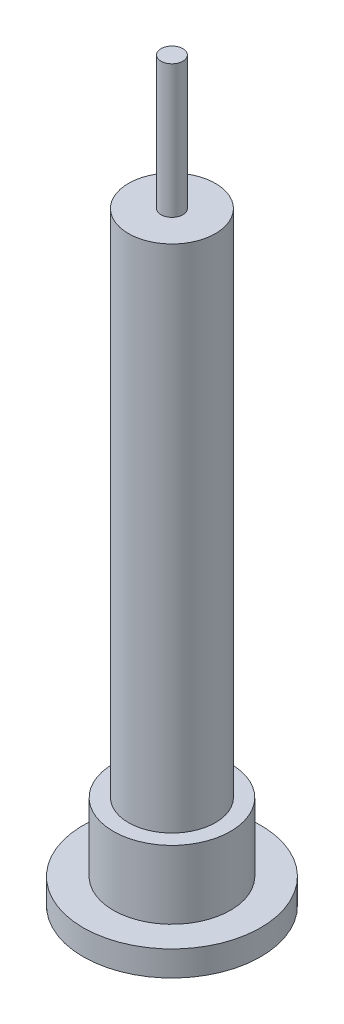
SolidWorks part; units mm, degrees
material "1060 Alloy"
ref_plane "Front Plane" through (0, 0, 0) normal (0, 0, 1) x (1, 0, 0)
ref_plane "Top Plane" through (0, 0, 0) normal (0, 1, 0) x (1, 0, 0)
ref_plane "Right Plane" through (0, 0, 0) normal (1, 0, 0) x (0, 0, -1)
sketch "Sketch1" plane through (0, 0, 0) normal (0, 0, 1) x (1, 0, 0)
  line L16 (0, 0) -> (3, 0)
  line L17 (3, 0) -> (3, 1.936)
  line L18 (3, 1.936) -> (10, 1.936)
  line L19 (10, 1.936) -> (10, 4.776)
  line L20 (10, 4.776) -> (6.6, 4.776)
  line L21 (6.6, 4.776) -> (6.6, 12.476)
  line L22 (6.6, 12.476) -> (4.9, 12.476)
  line L23 (4.9, 12.476) -> (4.9, 69.9525)
  line L24 (4.9, 69.9525) -> (1.2286, 69.9525)
  line L25 (1.2286, 69.9525) -> (1.2286, 84.936)
  line L26 (1.2286, 84.936) -> (0, 84.936)
  line L27 (0, 84.936) -> (0, 0)
  dimension "D1" = 3
  dimension "D2" = 7
  dimension "D3" = 2.84
  dimension "D4" = 83
  dimension "D5" = 3.4
  dimension "D6" = 7.7
  dimension "D7" = 4.9
revolve "Revolve1" add sketch "Sketch1" angle 360 about L27
